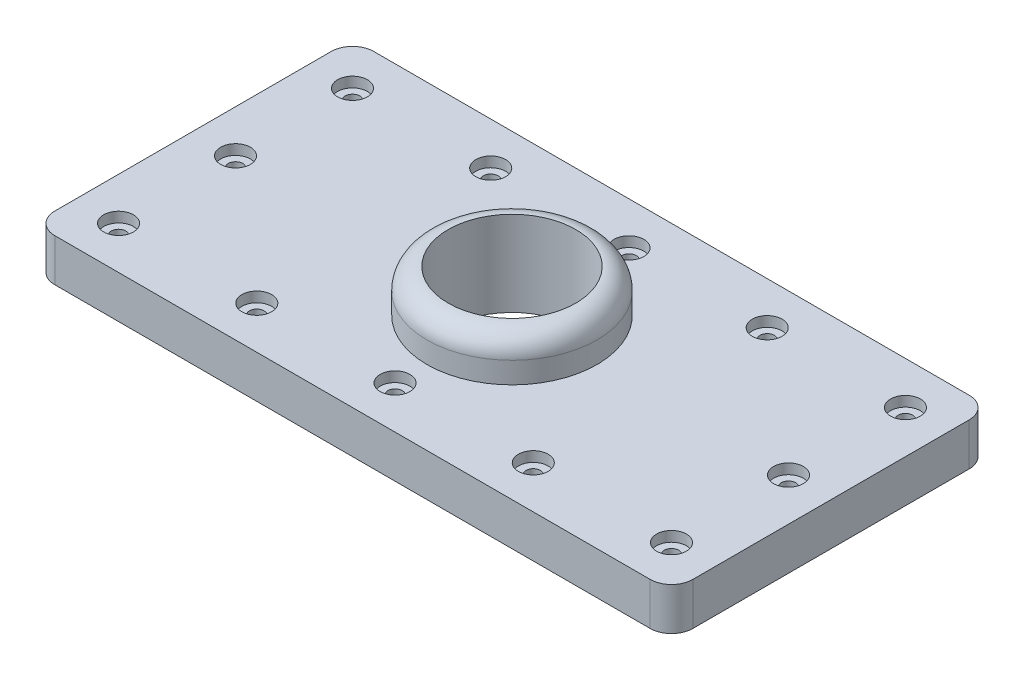
SolidWorks part; units mm, degrees
ref_plane "Plan de face" through (0, 0, 0) normal (0, 0, 1) x (1, 0, 0)
ref_plane "Plan de dessus" through (0, 0, 0) normal (0, 1, 0) x (1, 0, 0)
ref_plane "Plan de droite" through (0, 0, 0) normal (1, 0, 0) x (0, 0, -1)
sketch "Profil Base" plane through (0, 0, 0) normal (0, 1, 0) x (1, 0, 0)
  line L1 (-75, 37.5) -> (75, 37.5)
  line L2 (-75, 37.5) -> (-75, -37.5)
  line L3 (-75, -37.5) -> (75, -37.5)
  line L4 (75, 37.5) -> (75, -37.5)
  line L5 (-75, 37.5) -> (75, -37.5) construction
  line L6 (-75, -37.5) -> (75, 37.5) construction
  point P0 (0, 0)
  dimension "D1" = 150
  dimension "D2" = 75
extrude "Base" add sketch "Profil Base" along normal blind 10
sketch "Profil Cylindre" plane through (0, 10, 0) normal (0, 1, 0) x (1, 0, 0)
  circle A0 centre (0, 0) radius 20
  dimension "D1" = 40
extrude "Cylindre" add sketch "Profil Cylindre" along normal blind 10
fillet "Congé1" radius 5 5 edges at (0, 20, 20) (-75, 5, -37.5) (75, 5, 37.5) (-75, 5, 37.5) (75, 5, -37.5)
hole_wizard "Perçage central" positions "Esquisse3" profile "Esquisse5" hole size "M5" standard "Ansi Metric" end condition up to next
sketch "Esquisse3" plane through (0, 20, 0) normal (0, 1, 0) x (1, 0, 0)
  point P0 (0, 0)
sketch "Esquisse5" plane through (0, 20, 0) normal (1, 0, 0) x (0, 0, 1)
  line L0 (0, 0) -> (0, 20)
  line L1 (0, 20) -> (15, 20)
  line L2 (15, 20) -> (15, 0)
  line L5 (15, 0) -> (0, 0)
  line L11 (0, -6.35) -> (0, 107.95) construction
  dimension "Diamètre du perçage jusqu'au prochain" = 30
  dimension "Profondeur du perçage jusqu'au prochain" = 20
hole_wizard "Chambrage pour vis à tête ronde bombée M31" positions "Esquisse8" profile "Esquisse9" counterbore size "M3" standard "Ansi Metric" end condition up to next
sketch "Esquisse8" plane through (0, 10, 0) normal (0, 1, 0) x (1, 0, 0)
  line L0 (70, 37.5) -> (-70, 37.5) construction
  line L1 (-75, 32.5) -> (-75, -32.5) construction
  point P0 (-65, 27.5)
  dimension "D1" = 10
  dimension "D2" = 10
sketch "Esquisse9" plane through (-65, 10, -27.5) normal (1, 0, 0) x (0, 0, 1)
  line L0 (0, 0) -> (0, 10)
  line L1 (0, 10) -> (1.7, 10)
  line L3 (1.7, 10) -> (1.7, 2.4)
  line L4 (1.7, 2.4) -> (3.5, 2.4)
  line L5 (3.5, 2.4) -> (3.5, 0)
  line L7 (3.5, 0) -> (0, 0)
  line L11 (0, -6.35) -> (0, 107.95) construction
  dimension "Diamètre du perçage jusqu'au prochain" = 3.4
  dimension "Profondeur du perçage jusqu'au prochain" = 10
  dimension "Diamètre du chambrage" = 7
  dimension "Profondeur du chambrage" = 2.4
pattern_linear "Répétition linéaire1" count 5 spacing 32.5 along (1, 0, 0) count 3 spacing 27.5 along (0, 0, 1) skipping (1, 1), (2, 1), (3, 1) of "Chambrage pour vis à tête ronde bombée M31"
